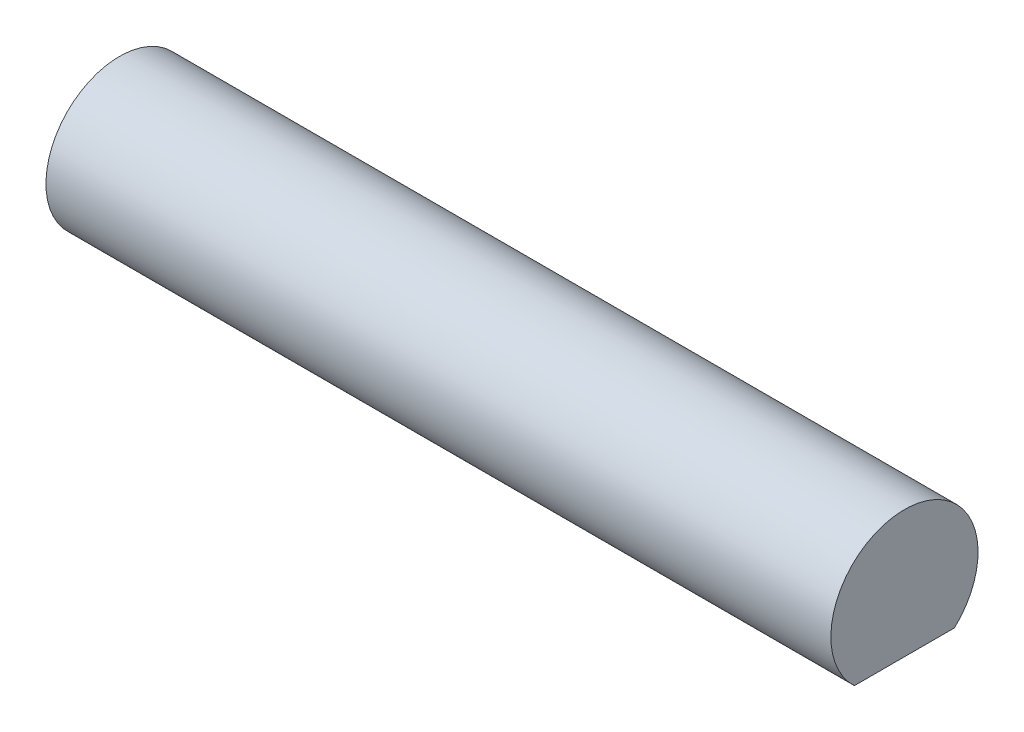
SolidWorks part; units mm, degrees
ref_plane "Front Plane" through (0, 0, 0) normal (0, 0, 1) x (1, 0, 0)
ref_plane "Top Plane" through (0, 0, 0) normal (0, 1, 0) x (1, 0, 0)
ref_plane "Right Plane" through (0, 0, 0) normal (1, 0, 0) x (0, 0, -1)
sketch "Sketch1" plane through (0, 0, 0) normal (1, 0, 0) x (0, 0, -1)
  line L0 (1.0198, -1.1) -> (-1.0198, -1.1)
  circle A0 centre (0, 0) radius 1.5
  dimension "D1" = 3
  dimension "D2" = 1.1
extrude "Boss-Extrude1" add sketch "Sketch1" along normal mid plane 16 contours L0 A0
